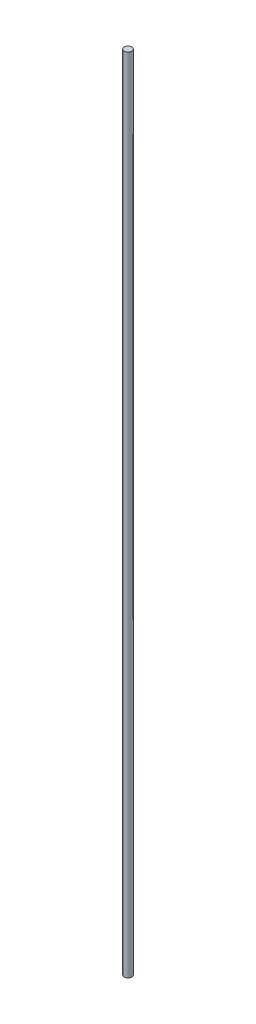
SolidWorks part; units mm, degrees
ref_plane "Front Plane" through (0, 0, 0) normal (0, 0, 1) x (1, 0, 0)
ref_plane "Top Plane" through (0, 0, 0) normal (0, 1, 0) x (1, 0, 0)
ref_plane "Right Plane" through (0, 0, 0) normal (1, 0, 0) x (0, 0, -1)
sketch "Sketch1" plane through (0, 0, 0) normal (0, 1, 0) x (1, 0, 0)
  circle A0 centre (0, 0) radius 4.7625
  dimension "D1" = 9.525
extrude "Boss-Extrude1" add sketch "Sketch1" along normal blind 1016
